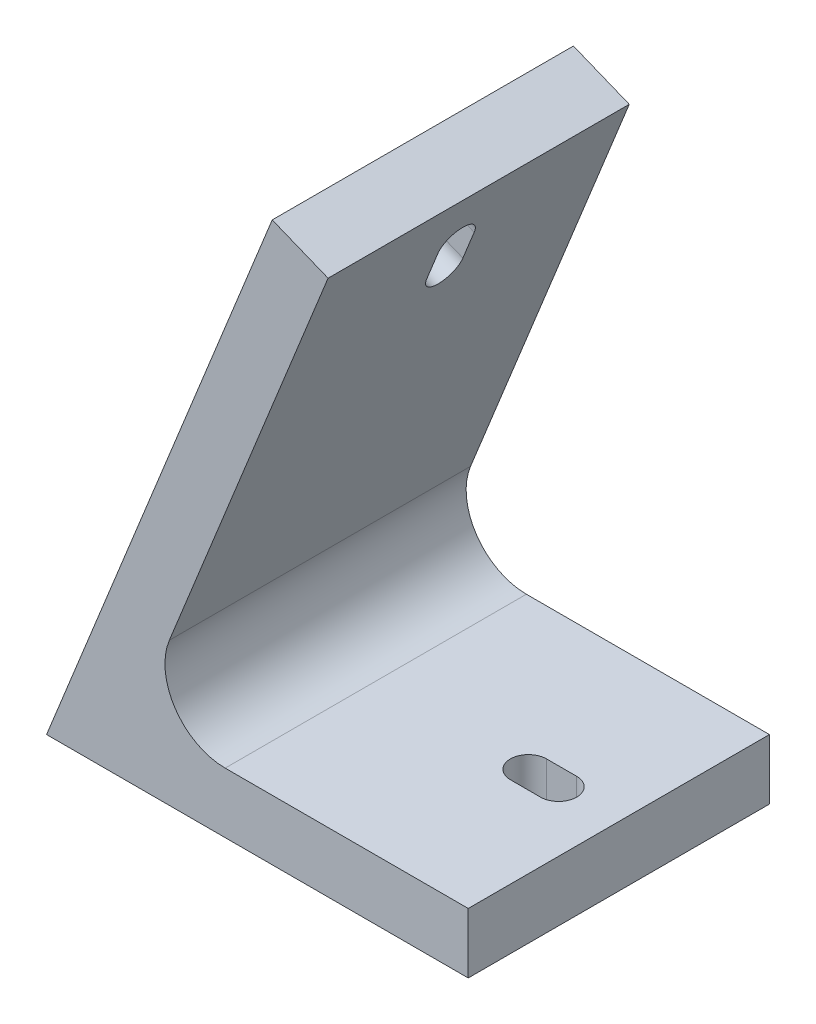
SolidWorks part; units mm, degrees
ref_plane "Front Plane" through (0, 0, 0) normal (0, 0, 1) x (1, 0, 0)
ref_plane "Top Plane" through (0, 0, 0) normal (0, 1, 0) x (1, 0, 0)
ref_plane "Right Plane" through (0, 0, 0) normal (1, 0, 0) x (0, 0, -1)
sketch "Sketch1" plane through (0, 0, 0) normal (0, 0, 1) x (1, 0, 0)
  line L0 (0, 0) -> (37.4607, 92.7184)
  line L1 (0, 0) -> (70, 0)
  line L2 (70, 0) -> (70, 10)
  line L3 (70, 10) -> (14.8256, 10)
  line L4 (14.8256, 10) -> (46.7325, 88.9723)
  line L5 (46.7325, 88.9723) -> (37.4607, 92.7184)
  dimension "D1" = 10
  dimension "D2" = 68
  dimension "D3" = 70
  dimension "D4" = 100
extrude "Boss-Extrude1" add sketch "Sketch1" along normal mid plane 50
sketch "Sketch2" plane through (0, 10, 0) normal (0, 1, 0) x (1, 0, 0)
  line L0 (60, 0) -> (55, 0) construction
  line L1 (60, -3) -> (55, -3)
  line L2 (60, 3) -> (55, 3)
  line L3 (70, -25) -> (70, 25) construction
  arc A0 (60, -3) -> (60, 3) centre (60, 0) ccw
  arc A1 (55, 3) -> (55, -3) centre (55, 0) ccw
  point P3 (57.5, 0)
  dimension "D3" = 3
  dimension "D1" = 5
  dimension "D2" = 10
extrude "Cut-Extrude1" cut sketch "Sketch2" against normal through all
sketch "Sketch3" plane through (9.2718, -3.7461, 0) normal (0.9272, -0.3746, 0) x (0, 0, -1)
  line L0 (0, 90) -> (0, 85) construction
  line L1 (3, 90) -> (3, 85)
  line L2 (-3, 90) -> (-3, 85)
  line L3 (-25, 100) -> (25, 100) construction
  arc A0 (3, 90) -> (-3, 90) centre (0, 90) ccw
  arc A1 (-3, 85) -> (3, 85) centre (0, 85) ccw
  point P3 (0, 87.5)
  dimension "D2" = 3
  dimension "D1" = 5
  dimension "D3" = 10
extrude "Cut-Extrude2" cut sketch "Sketch3" against normal through all
fillet "Fillet1" [suppressed] radius 1
fillet "Fillet2" radius 10 1 edges at (14.8256, 10, 0)
